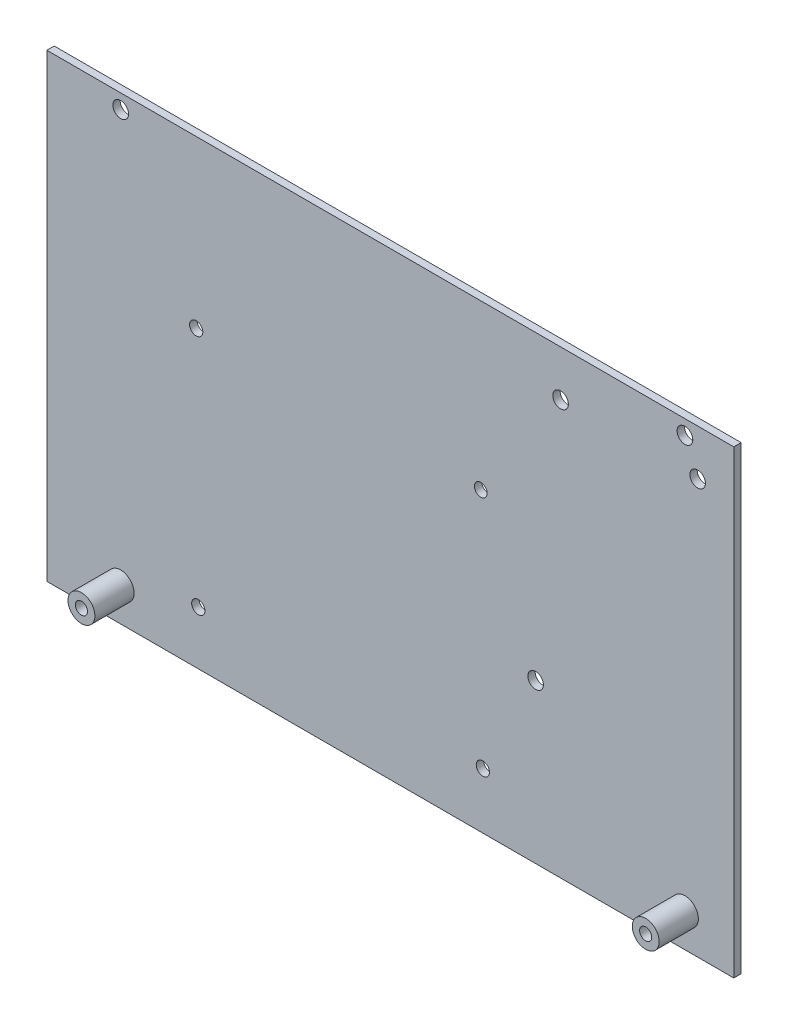
SolidWorks part; units mm, degrees
ref_plane "Front Plane" through (0, 0, 0) normal (0, 0, 1) x (1, 0, 0)
ref_plane "Top Plane" through (0, 0, 0) normal (0, 1, 0) x (1, 0, 0)
ref_plane "Right Plane" through (0, 0, 0) normal (1, 0, 0) x (0, 0, -1)
sketch "Sketch1" plane through (0, 0, 0) normal (0, 0, 1) x (1, 0, 0)
  line L0 (32, 242.9727) -> (172, 242.9727)
  line L1 (32, 242.9727) -> (32, 149.2189)
  line L2 (172, 242.9727) -> (172, 149.2189)
  line L3 (32, 149.2189) -> (172, 149.2189)
  line L4 (29, 242.9727) -> (174.2, 242.9727) construction
  line L5 (29, 242.9727) -> (29, 240.0279) construction
  dimension "D1" = 140
  dimension "D2" = 3
extrude "Boss-Extrude1" add sketch "Sketch1" along normal blind 1.5
sketch "Sketch2" plane through (0, 0, 1.5) normal (0, 0, 1) x (1, 0, 0)
  circle A0 centre (47.044, 240.0279) radius 1.6
  circle A1 centre (162.044, 240.0279) radius 1.6
extrude "Cut-Extrude1" cut sketch "Sketch2" against normal blind 1.5
sketch "Sketch3" plane through (0, 0, 1.5) normal (0, 0, 1) x (1, 0, 0)
  circle A0 centre (47.044, 156.0279) radius 1.2376
  circle A1 centre (162.044, 156.0279) radius 1.2376
  circle A2 centre (47.044, 156.0279) radius 2.7376
  circle A3 centre (162.044, 156.0279) radius 2.7376
  dimension "D1" = 1.5
extrude "Boss-Extrude2" add sketch "Sketch3" along normal blind 8
sketch "Sketch4" plane through (0, 0, 0) normal (0, 0, -1) x (-1, 0, 0)
  circle A0 centre (-120.4318, 209.6172) radius 1.3
  circle A1 centre (-62.434, 209.1111) radius 1.35
  circle A2 centre (-62.8616, 160.1129) radius 1.35
  circle A3 centre (-120.8594, 160.6191) radius 1.35
  circle A4 centre (-131.6131, 181.5519) radius 1.5875
  circle A5 centre (-136.6931, 233.6219) radius 1.5875
  circle A6 centre (-164.6331, 233.6219) radius 1.5875
extrude "Cut-Extrude2" cut sketch "Sketch4" against normal blind 8
